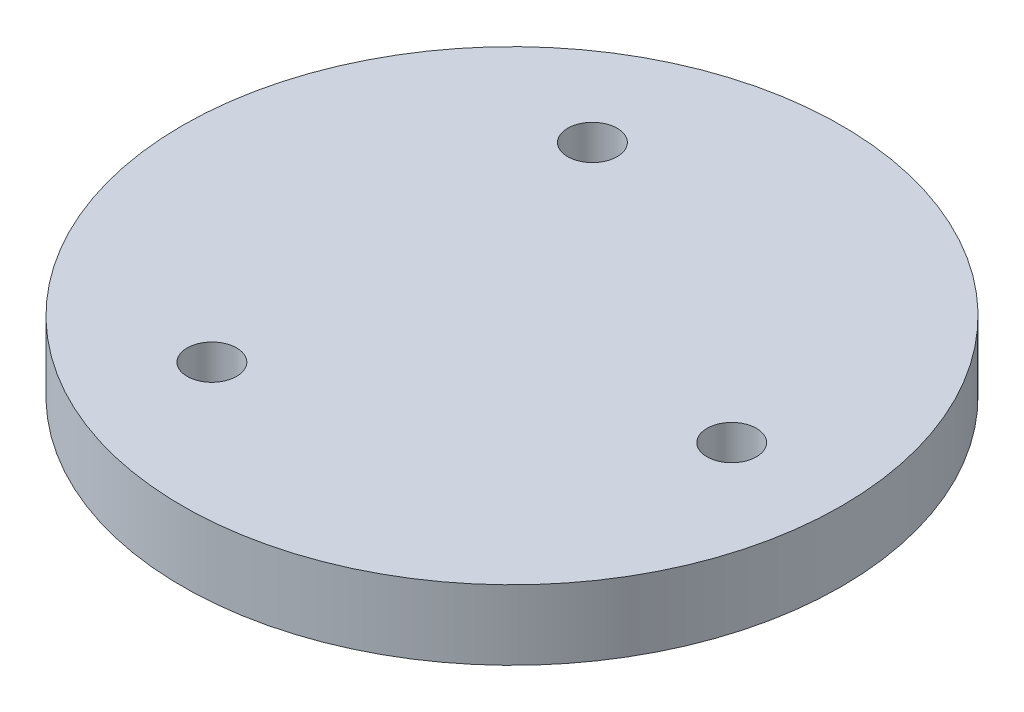
SolidWorks part; units mm, degrees
material "AISI 304"
ref_plane "Front Plane" through (0, 0, 0) normal (0, 0, 1) x (1, 0, 0)
ref_plane "Top Plane" through (0, 0, 0) normal (0, 1, 0) x (1, 0, 0)
ref_plane "Right Plane" through (0, 0, 0) normal (1, 0, 0) x (0, 0, -1)
sketch "Sketch1" plane through (0, 0, 0) normal (0, 0, 1) x (1, 0, 0)
  line L2 (0, 3.175) -> (-30, 3.175)
  line L3 (-30, 3.175) -> (-30, -3.175)
  line L4 (-30, -3.175) -> (0, -3.175)
  line L5 (0, -3.175) -> (0, 3.175)
  point P1 (0, 0)
  point P2 (-7.8236, 0)
  point P7 (-5.647, 0)
  point P9 (-5.647, -0.4146)
  dimension "D1" = 6.35
  dimension "D2" = 30
revolve "Revolve1" add sketch "Sketch1" angle 360 about L5
hole_wizard "M4 Clearance Hole1" positions "Sketch5" profile "Sketch6" hole size "M4" standard "ANSI Metric"
sketch "Sketch5" plane through (0, -3.175, 0) normal (0, -1, 0) x (-1, 0, 0)
  line L0 (-20, 0) -> (0, 0) construction
  line L1 (0, 0) -> (10, -17.3205) construction
  line L3 (0, 0) -> (10, 17.3205) construction
  point P1 (-20, 0)
  point P5 (10, -17.3205)
  point P10 (10, 17.3205)
  dimension "D1" = 120
  dimension "D2" = 120
  dimension "D3" = 20
sketch "Sketch6" plane through (20, -3.175, 0) normal (1, 0, 0) x (0, 0, -1)
  line L0 (0, 0) -> (0, 11.4519)
  line L1 (0, 11.4519) -> (2.25, 10.1)
  line L2 (2.25, 10.1) -> (2.25, 0)
  line L5 (2.25, 0) -> (0, 0)
  line L10 (0, 11.4519) -> (-2.25, 10.1) construction
  line L11 (0, -6.35) -> (0, 107.95) construction
  dimension "Hole Dia." = 4.5
  dimension "Hole Depth" = 10.1
  dimension "Drill Angle" = 118
